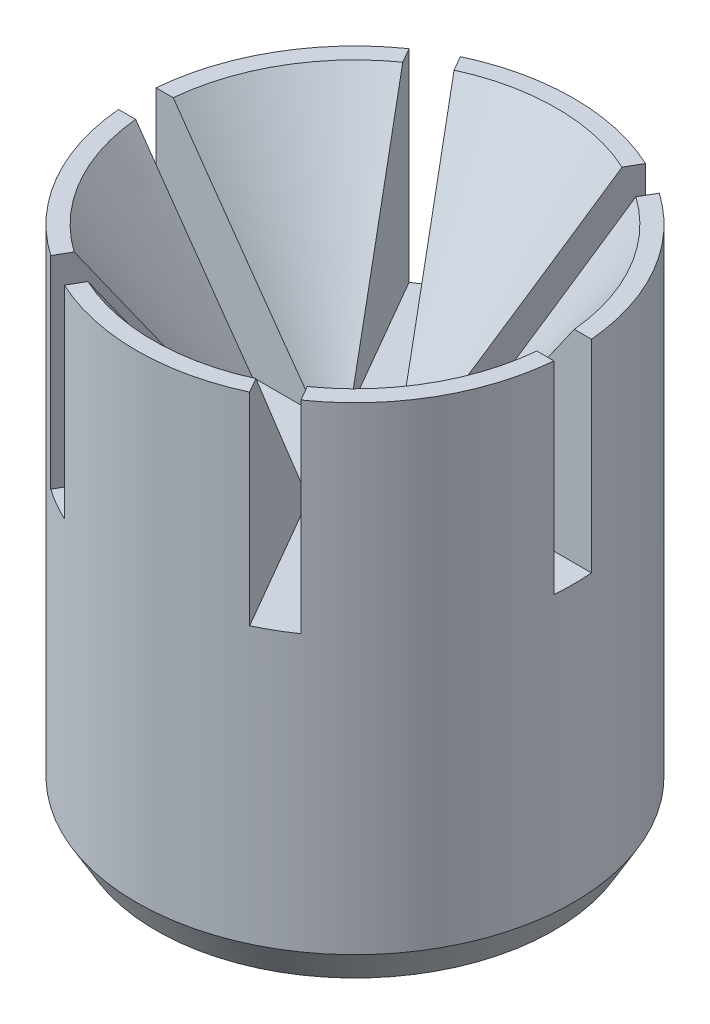
SolidWorks part; units mm, degrees
ref_plane "Front Plane" through (0, 0, 0) normal (0, 0, 1) x (1, 0, 0)
ref_plane "Top Plane" through (0, 0, 0) normal (0, 1, 0) x (1, 0, 0)
ref_plane "Right Plane" through (0, 0, 0) normal (1, 0, 0) x (0, 0, -1)
sketch "Sketch1" plane through (0, 0, 0) normal (0, 0, 1) x (1, 0, 0)
  line L0 (0, 0) -> (0, 0.5)
  line L1 (0, 0) -> (2.7, 0)
  line L2 (2.7, 0) -> (2.7, -4)
  line L3 (2.7, -4) -> (6.4, -4)
  line L4 (6.4, -4) -> (6.4, 11)
  line L6 (0, 0.5) -> (0.75, 0.5)
  line L7 (0.75, 0.5) -> (0.75, 5.0732)
  line L8 (0.75, 5.0732) -> (1.75, 5.0732)
  line L10 (6.4, 11) -> (5.9, 11)
  line L11 (5.9, 11) -> (1.75, 5.0732)
  dimension "D1" = 2.7
  dimension "D2" = 4
  dimension "D3" = 6.4
  dimension "D4" = 0.75
  dimension "D5" = 0.5
  dimension "D6" = 1
  dimension "D7" = 0.5
  dimension "D8" = 35
  dimension "D9" = 11
revolve "Revolve1" add sketch "Sketch1" angle 360 about L0
sketch "Sketch2" plane through (0, 0, 0) normal (0, 0, -1) x (-1, 0, 0)
  line L0 (6.4, 11) -> (-6.4, 11) construction
  line L1 (0, 11) -> (-6.4, 11)
  line L2 (0, 11) -> (0, 5.0732)
  line L3 (0, 5.0732) -> (-6.4, 5.0732)
  line L4 (-6.4, 11) -> (-6.4, 5.0732)
  line L5 (-3.2, 5.0732) -> (-3.2, 11) construction
  line L6 (0, 8.0366) -> (-6.4, 8.0366) construction
  line L7 (-6.4, 11) -> (-6.4, -4) construction
  line L8 (0.75, 5.0732) -> (-0.75, 5.0732) construction
  point P304 (-3.2, 8.0366)
chamfer "Chamfer1" distance 1 angle 30 1 edges at (0, -4, -6.4)
extrude "Cut-Extrude1" cut sketch "Sketch2" against normal mid plane 1.1
pattern_circular "CirPattern1" count 6 over 360 about axis through (0, 0, 0) along (0, 1, 0) of "Cut-Extrude1"
